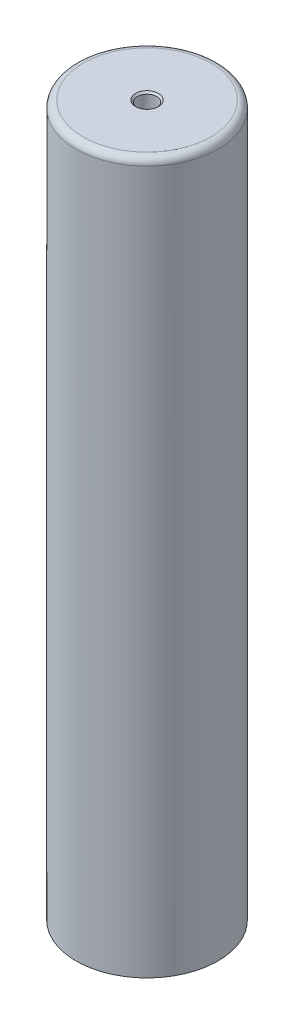
SolidWorks part; units mm, degrees
material "AISI 316 Stainless Steel Sheet (SS)"
ref_plane "Front Plane" through (0, 0, 0) normal (0, 0, 1) x (1, 0, 0)
ref_plane "Top Plane" through (0, 0, 0) normal (0, 1, 0) x (1, 0, 0)
ref_plane "Right Plane" through (0, 0, 0) normal (1, 0, 0) x (0, 0, -1)
sketch "Sketch1" plane through (0, 0, 0) normal (0, 0, 1) x (1, 0, 0)
  line L0 (0, 0) -> (0, 314.9411) construction
  line L1 (0, 250) -> (25, 250)
  line L2 (25, 250) -> (25, 0)
  line L3 (25, 0) -> (0, 0)
  line L4 (0, 0) -> (0, 250)
  dimension "D1" = 50
  dimension "D2" = 250
revolve "Revolve1" add sketch "Sketch1" angle 360 about L0
sketch "Sketch2" plane through (0, 250, 0) normal (0, 1, 0) x (1, 0, 0)
  point P0 (0, 0)
hole_wizard "M8 Tapped Hole1" positions "3DSketch1" profile "Sketch3" tap size "M8" standard "ISO"
sketch3d "3DSketch1"
  point P0 (0, 250, 0)
sketch "Sketch3" plane through (0, 250, 0) normal (1, 0, 0) x (0, 0, 1)
  line L0 (0, 0) -> (0, 18.7929)
  line L1 (0, 18.7929) -> (3.4, 16.75)
  line L2 (3.4, 16.75) -> (3.4, 0.625)
  line L3 (3.4, 0.625) -> (4.025, 0)
  line L5 (4.025, 0) -> (0, 0)
  line L6 (-3.4, 0.625) -> (-4.025, 0) construction
  line L10 (0, 18.7929) -> (-3.4, 16.75) construction
  line L11 (0, -6.35) -> (0, 107.95) construction
  dimension "Tap Drill Dia." = 6.8
  dimension "Tap Drill Depth" = 16.75
  dimension "Near C'Sink Dia." = 8.05
  dimension "Near C'Sink Angle" = 90
  dimension "Drill Angle" = 118
cosmetic thread "Hole Thread1" parameters "D1"=13, "D2"=8
fillet "Fillet1" radius 2.5 1 edges at (0, 250, -25)
